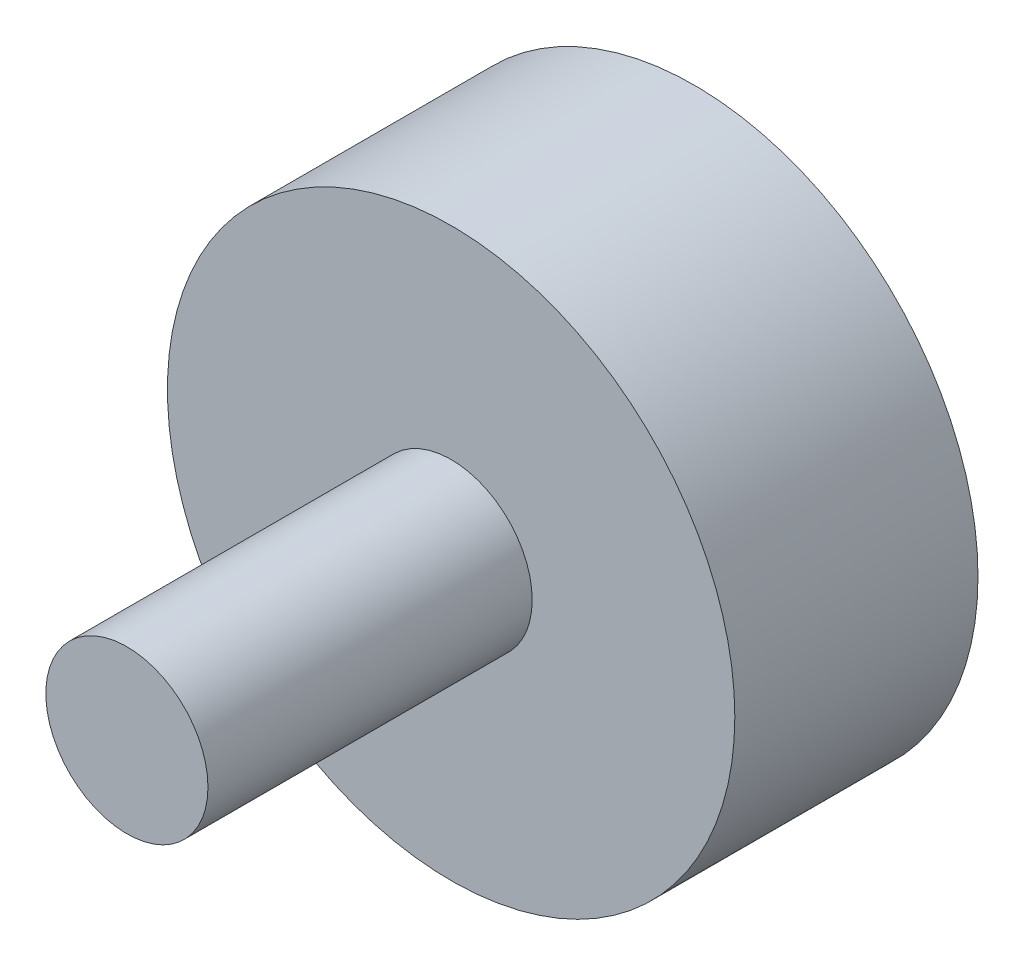
SolidWorks part; units mm, degrees
ref_plane "Front Plane" through (0, 0, 0) normal (0, 0, 1) x (1, 0, 0)
ref_plane "Top Plane" through (0, 0, 0) normal (0, 1, 0) x (1, 0, 0)
ref_plane "Right Plane" through (0, 0, 0) normal (1, 0, 0) x (0, 0, -1)
sketch "Sketch1" plane through (0, 0, 0) normal (0, 0, 1) x (1, 0, 0)
  circle A0 centre (0, 0) radius 3.5
  dimension "D1" = 7
extrude "Boss-Extrude1" add sketch "Sketch1" along normal blind 3
sketch "Sketch2" plane through (0, 0, 3) normal (0, 0, 1) x (1, 0, 0)
  circle A0 centre (0, 0) radius 1
  dimension "D1" = 2
extrude "Boss-Extrude2" add sketch "Sketch2" along normal blind 4
